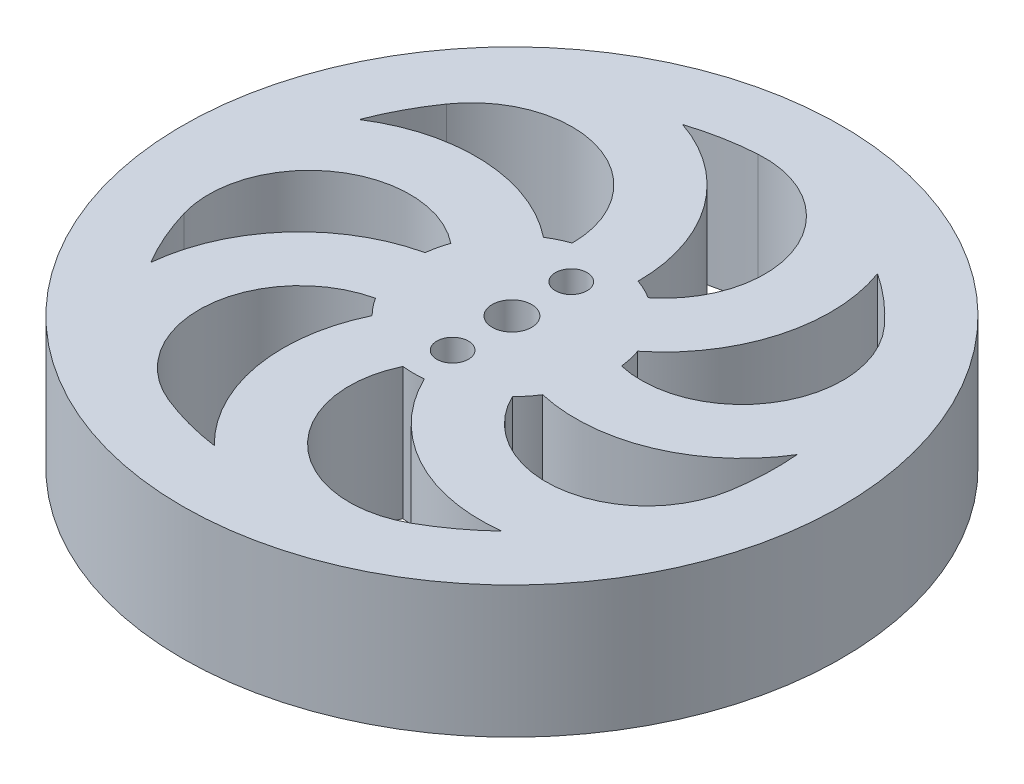
SolidWorks part; units mm, degrees
material "Rubber"
ref_plane "Front Plane" through (0, 0, 0) normal (0, 0, 1) x (1, 0, 0)
ref_plane "Top Plane" through (0, 0, 0) normal (0, 1, 0) x (1, 0, 0)
ref_plane "Right Plane" through (0, 0, 0) normal (1, 0, 0) x (0, 0, -1)
sketch "Base Reference Sketch" plane through (0, 0, 0) normal (0, 1, 0) x (1, 0, 0)
  line L0 (-2.5, 7.0711) -> (2.5, 7.0711) construction
  line L1 (0, 7.5) -> (0, 1.5) construction
  circle A0 centre (0, 0) radius 25
  circle A1 centre (0, 0) radius 20
  circle A2 centre (0, 0) radius 1.5
  circle A3 centre (0, 0) radius 7.5
  arc A4 (-2.5, 7.0711) -> (-16.4045, 11.4408) centre (-10.1389, 7.0711) ccw
  arc A5 (2.5, 7.0711) -> (-6.0997, 19.0471) centre (-10.1389, 7.0711) ccw
  arc A6 (2.5, 7.0711) -> (-20.5056, 14.301) centre (-10.1389, 7.0711) ccw construction
  circle A7 centre (0, 0) radius 7.5 construction
  point P14 (0, 4.5)
  point P15 (0, 3.5)
  dimension "D1" = 50
  dimension "D3" = 6
  dimension "D2" = 5
  dimension "D4" = 3
  dimension "D5" = 5
  dimension "D6" = 0
extrude "Base Wheel Extrude" add sketch "Base Reference Sketch" along normal blind 10 contours A0 A1 | A3 A5 A1 A4 | A3 A2
pattern_circular "Spokes Circular Pattern" count 7 over 360 about axis through (0, 0, 0) along (0, 1, 0) of "Base Wheel Extrude"
hole_wizard "M2 Clearance Hole1" positions "Sketch1" profile "Sketch2" hole size "M2" standard "ISO" end condition through all
sketch "Sketch1" plane through (0, 0, 0) normal (0, -1, 0) x (-1, 0, 0)
  point P0 (0, 4.5)
sketch "Sketch2" plane through (0, 0, -4.5) normal (1, 0, 0) x (0, 0, -1)
  line L0 (0, 0) -> (0, 10)
  line L1 (0, 10) -> (1.2, 10)
  line L2 (1.2, 10) -> (1.2, 0)
  line L5 (1.2, 0) -> (0, 0)
  line L11 (0, -6.35) -> (0, 107.95) construction
  dimension "Thru Hole Dia." = 2.4
  dimension "Thru Hole Depth" = 10
pattern_circular "CirPattern1" count 2 over 360 about axis through (0, 0, 0) along (0, 1, 0) of "M2 Clearance Hole1"
equation "\"wheeldia\"= 50mm"
equation "\"wheelthick\"= 3mm"
equation "\"wheelwide\"= 10mm"
equation "\"wheelspokes\"= 7"
